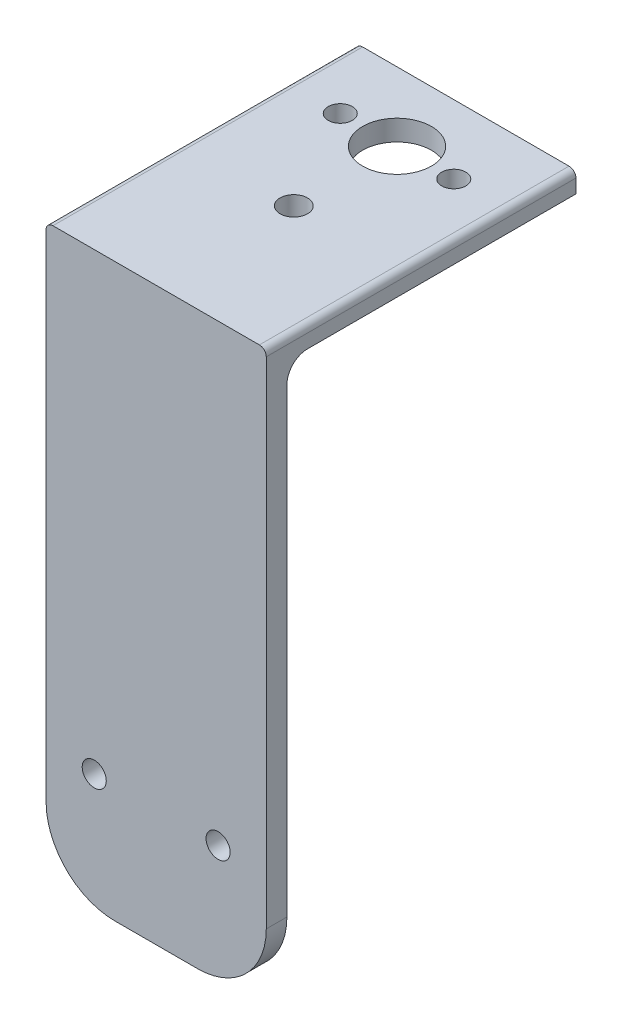
SolidWorks part; units mm, degrees
material "ABS"
ref_plane "Alzado" through (0, 0, 0) normal (0, 0, 1) x (1, 0, 0)
ref_plane "Planta" through (0, 0, 0) normal (0, 1, 0) x (1, 0, 0)
ref_plane "Vista lateral" through (0, 0, 0) normal (1, 0, 0) x (0, 0, -1)
sketch "Croquis1" plane through (0, 0, 0) normal (0, 1, 0) x (1, 0, 0)
  line L1 (-16, -22.5) -> (16, -22.5)
  line L2 (-16, -22.5) -> (-16, 22.5)
  line L3 (-16, 22.5) -> (16, 22.5)
  line L4 (16, -22.5) -> (16, 22.5)
  line L5 (-16, -22.5) -> (16, 22.5) construction
  line L6 (-16, 22.5) -> (16, -22.5) construction
  circle A0 centre (0, 12.5) radius 5
  point P0 (0, 0)
  dimension "D3" = 10
  dimension "D1" = 32
  dimension "D2" = 45
  dimension "D4" = 10
extrude "Saliente-Extruir1" add sketch "Croquis1" along normal blind 3
sketch "Croquis2" plane through (0, 0, 0) normal (0, -1, 0) x (1, 0, 0)
  line L0 (16, 22.5) -> (16, -22.5) construction
  line L1 (-16, 22.5) -> (16, 22.5)
  line L2 (-16, 22.5) -> (-16, 19.5)
  line L3 (-16, 19.5) -> (16, 19.5)
  line L4 (16, 22.5) -> (16, 19.5)
  dimension "D1" = 3
extrude "Saliente-Extruir2" add sketch "Croquis2" along normal blind 80
fillet "Redondeo1" radius 3 1 edges at (0, 0, 19.5)
fillet "Redondeo3" radius 1 2 edges at (16, 3, 0) (-16, 3, 0)
sketch "Croquis5" plane through (0, 3, 0) normal (0, 1, 0) x (1, 0, 0)
  line L0 (-8.25, 12.5) -> (8.25, 12.5)
  circle A0 centre (0, 12.5) radius 5 construction
  circle A1 centre (-8.25, 12.5) radius 1.75
  circle A2 centre (8.25, 12.5) radius 1.75
  point P4 (0, 12.5)
  dimension "D2" = 8.25
  dimension "D3" = 3.5
  dimension "D4" = 3.5
  dimension "D1" = 16.5
  dimension "D5" = 0
extrude "Cortar-Extruir2" cut sketch "Croquis5" against normal blind 10
sketch "Croquis6" plane through (0, 0, 22.5) normal (0, 0, 1) x (1, 0, 0)
  line L0 (16, -80) -> (-16, -80) construction
  line L1 (-16, 2) -> (-16, -80) construction
  line L2 (16, 2) -> (16, -80) construction
  circle A0 centre (-9, -63) radius 1.75
  circle A1 centre (9, -63) radius 1.75
  dimension "D1" = 3.5
  dimension "D2" = 3.5
  dimension "D3" = 17
  dimension "D4" = 17
  dimension "D5" = 7
  dimension "D6" = 7
extrude "Cortar-Extruir3" cut sketch "Croquis6" against normal blind 10
fillet "Redondeo4" radius 10 2 edges at (16, -80, 21) (-16, -80, 21)
sketch "Croquis7" plane through (0, 3, 0) normal (0, 1, 0) x (1, 0, 0)
  circle A0 centre (0, -2.5) radius 2
  circle A1 centre (0, 12.5) radius 5 construction
  dimension "D1" = 4
  dimension "D2" = 15
extrude "Cortar-Extruir4" cut sketch "Croquis7" against normal blind 10
